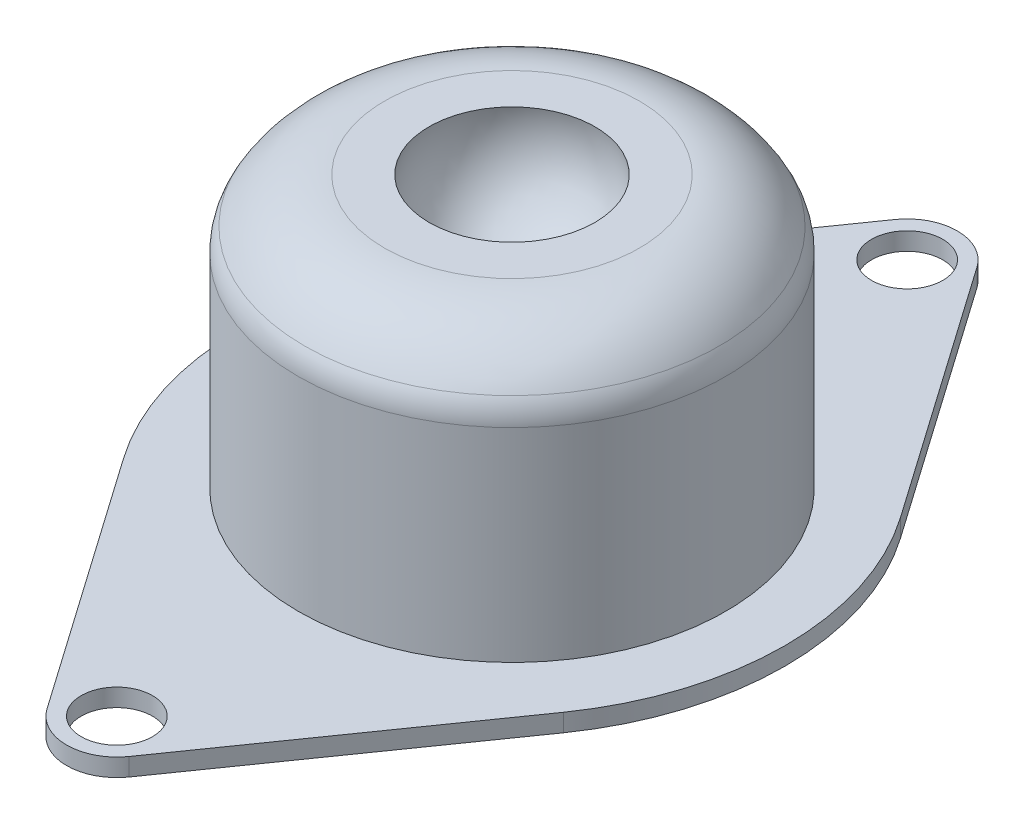
SolidWorks part; units mm, degrees
material "Cast Alloy Steel"
ref_plane "Front Plane" through (0, 0, 0) normal (0, 0, 1) x (1, 0, 0)
ref_plane "Top Plane" through (0, 0, 0) normal (0, 1, 0) x (1, 0, 0)
ref_plane "Right Plane" through (0, 0, 0) normal (1, 0, 0) x (0, 0, -1)
sketch "Sketch1" plane through (0, 0, 0) normal (0, 1, 0) x (1, 0, 0)
  line L0 (-2.3068, 23.7992) -> (-12.3444, 9.464)
  line L1 (0, 25) -> (0, -25) construction
  line L2 (0, 0) -> (-15.3283, 0) construction
  line L3 (2.3068, 23.7992) -> (12.3444, 9.464)
  line L4 (2.3068, -23.7992) -> (12.3444, -9.464)
  line L5 (-2.3068, -23.7992) -> (-12.3444, -9.464)
  arc A0 (-2.3068, 23.7992) -> (2.3068, 23.7992) centre (0, 22.184) cw
  arc A1 (-12.3444, 9.464) -> (-12.3444, -9.464) centre (1.1717, 0) ccw
  arc A2 (12.3444, 9.464) -> (12.3444, -9.464) centre (-1.1717, 0) cw
  arc A3 (-2.3068, -23.7992) -> (2.3068, -23.7992) centre (0, -22.184) ccw
  point P6 (0, 18.5211)
  point P7 (-14.3263, 0)
  point P10 (0, 13.1509)
  point P11 (-0.6871, 1.7207)
  point P12 (-1.251, 0.9464)
  point P22 (-1.0823, -0.9464)
  point P23 (0, 0)
  point P24 (-1.3807, 0)
  point P25 (-1.2131, -0.9464)
  dimension "D2" = 16.5
  dimension "D1" = 35
  dimension "D3" = 50
  dimension "D4" = 17.5
extrude "Boss-Extrude1" add sketch "Sketch1" along normal blind 1
sketch "Sketch3" plane through (0, 0, 0) normal (0, 0, 1) x (1, 0, 0)
  line L0 (0, 1) -> (12, 1)
  line L1 (12, 1) -> (12, 13)
  line L4 (15.3283, 1) -> (12.3444, 1) construction
  line L5 (7.1563, 16.2375) -> (4.6563, 16.2375)
  line L6 (0, 10.475) -> (0, 1)
  circle A0 centre (0, 15.2375) radius 4.7625 construction
  arc A1 (4.6563, 16.2375) -> (0, 10.475) centre (0, 15.2375) cw
  arc A2 (7.1563, 16.2375) -> (12, 13) centre (7.1563, 10.9954) cw
  point P2 (0, 20)
  point P10 (4.6563, 16.2375)
  dimension "D3" = 9.525
  dimension "D1" = 12
  dimension "D2" = 1
  dimension "D4" = 20
  dimension "D5" = 12
  dimension "D6" = 2.5
revolve "Revolve1" add sketch "Sketch3" angle 360 about L6
fillet "Fillet2" radius 2.5 1 edges at (0, 13, 12)
sketch "Sketch4" plane through (0, 1, 0) normal (0, 1, 0) x (1, 0, 0)
  circle A0 centre (0, -22.184) radius 2
  circle A1 centre (0, 22.184) radius 2
  arc A2 (-2.3068, -23.7992) -> (2.3068, -23.7992) centre (0, -22.184) ccw construction
  arc A3 (2.3068, 23.7992) -> (-2.3068, 23.7992) centre (0, 22.184) ccw construction
  dimension "D1" = 4
extrude "Cut-Extrude1" cut sketch "Sketch4" against normal through all
